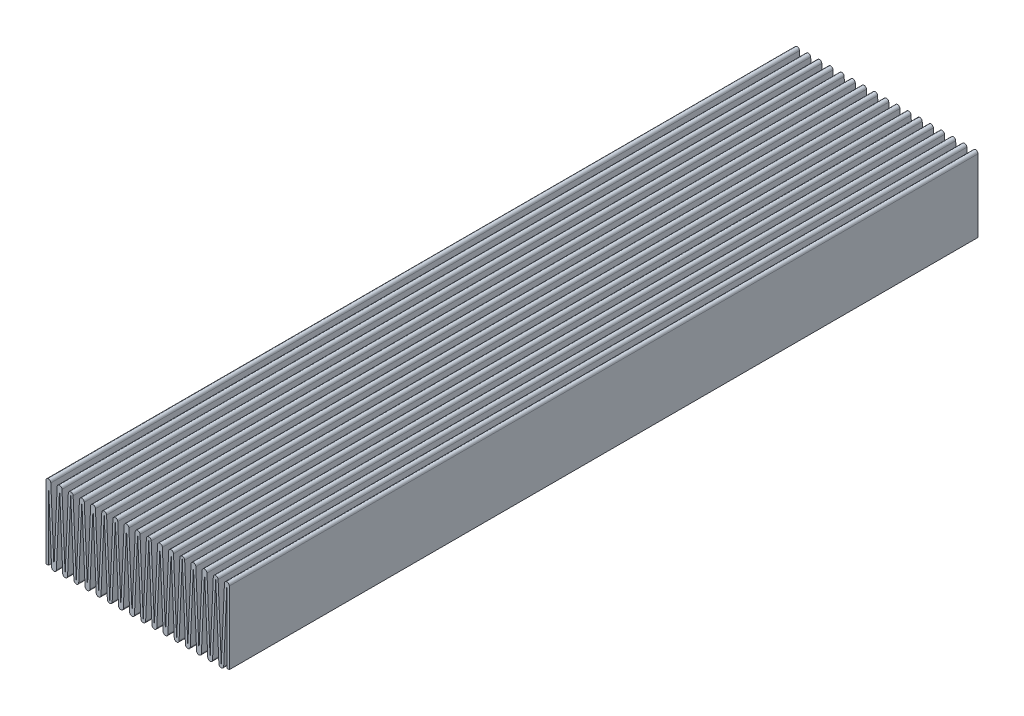
SolidWorks part; units mm, degrees
ref_plane "前视基准面" through (0, 0, 0) normal (0, 0, 1) x (1, 0, 0)
ref_plane "上视基准面" through (0, 0, 0) normal (0, 1, 0) x (1, 0, 0)
ref_plane "右视基准面" through (0, 0, 0) normal (1, 0, 0) x (0, 0, -1)
sketch "草图1" plane through (0, 0, 0) normal (0, 0, 1) x (1, 0, 0)
  line L0 (0.5, 15) -> (1.1549, 0)
  line L1 (0, 0) -> (0.5, 0)
  line L2 (0, 0) -> (0, 15)
  line L3 (0, 15) -> (0.5, 15)
  line L4 (0.5, 0) -> (0.5, 15)
  line L5 (0, 0) -> (0.5, 15) construction
  line L6 (0, 15) -> (0.5, 0) construction
  line L7 (0.5, 15) -> (0.9995, 15.0218)
  line L8 (1.1549, 0) -> (1.6544, 0.0218)
  line L9 (0.9995, 15.0218) -> (1.6544, 0.0218)
  line L10 (1.6544, 0.0218) -> (1.6544, -1.5324)
  line L11 (2.3094, 15.0218) -> (1.6544, 0.0218)
  line L12 (2.8089, 15) -> (2.154, 0)
  line L13 (2.8089, 15) -> (2.8089, 16.4409)
  line L14 (3.3084, 15.0218) -> (3.9633, 0.0218)
  line L15 (2.8089, 15) -> (3.4638, 0)
  line L16 (5.1178, 15) -> (4.4628, 0)
  line L17 (4.6182, 15.0218) -> (3.9633, 0.0218)
  line L18 (5.1178, 15) -> (5.1178, 16.4409)
  line L19 (5.6173, 15.0218) -> (6.2722, 0.0218)
  line L20 (5.1178, 15) -> (5.7727, 0)
  line L21 (7.4266, 15) -> (6.7717, 0)
  line L22 (6.9271, 15.0218) -> (6.2722, 0.0218)
  line L23 (7.9262, 15.0218) -> (8.5811, 0.0218)
  line L24 (7.4266, 15) -> (8.0815, 0)
  line L25 (9.7355, 15) -> (9.0806, 0)
  line L26 (9.236, 15.0218) -> (8.5811, 0.0218)
  line L27 (9.7355, 15) -> (9.7355, 16.4409)
  line L28 (18.971, 15) -> (18.971, 17.0964)
  line L29 (19.4705, 15.0218) -> (20.1255, 0.0218)
  line L30 (18.971, 15) -> (19.6259, 0)
  line L31 (10.235, 15.0218) -> (10.8899, 0.0218)
  line L32 (9.7355, 15) -> (10.3904, 0)
  line L33 (12.0444, 15) -> (11.3895, 0)
  line L34 (11.5449, 15.0218) -> (10.8899, 0.0218)
  line L35 (12.5439, 15.0218) -> (13.1988, 0.0218)
  line L36 (12.0444, 15) -> (12.6993, 0)
  line L37 (14.3533, 15) -> (13.6983, 0)
  line L38 (13.8537, 15.0218) -> (13.1988, 0.0218)
  line L39 (14.8528, 15.0218) -> (15.5077, 0.0218)
  line L40 (14.3533, 15) -> (15.0082, 0)
  line L41 (16.6621, 15) -> (16.0072, 0)
  line L42 (16.1626, 15.0218) -> (15.5077, 0.0218)
  line L43 (17.1617, 15.0218) -> (17.8166, 0.0218)
  line L44 (16.6621, 15) -> (17.317, 0)
  line L45 (18.971, 15) -> (18.3161, 0)
  line L46 (18.4715, 15.0218) -> (17.8166, 0.0218)
  line L47 (21.2799, 15) -> (20.625, 0)
  line L48 (20.7804, 15.0218) -> (20.1255, 0.0218)
  line L49 (21.7794, 15.0218) -> (22.4343, 0.0218)
  line L50 (21.2799, 15) -> (21.9348, 0)
  line L51 (23.5888, 15) -> (22.9339, 0)
  line L52 (23.0892, 15.0218) -> (22.4343, 0.0218)
  line L53 (24.0883, 15.0218) -> (24.7432, 0.0218)
  line L54 (23.5888, 15) -> (24.2437, 0)
  line L55 (25.3981, 15.0218) -> (24.7432, 0.0218)
  line L56 (25.8976, 15) -> (25.2427, 0)
  line L57 (26.3972, 15.0218) -> (27.0521, 0.0218)
  line L58 (25.8976, 15) -> (26.5526, 0)
  line L59 (27.707, 15.0218) -> (27.0521, 0.0218)
  line L60 (28.2065, 15) -> (27.5516, 0)
  line L61 (28.706, 15.0218) -> (29.361, 0.0218)
  line L62 (28.2065, 15) -> (28.8614, 0)
  line L63 (30.5154, 15) -> (29.8605, 0)
  line L64 (30.0159, 15.0218) -> (29.361, 0.0218)
  line L65 (31.0149, 15.0218) -> (31.6698, 0.0218)
  line L66 (30.5154, 15) -> (31.1703, 0)
  line L67 (32.8243, 15) -> (32.1694, 0)
  line L68 (32.3247, 15.0218) -> (31.6698, 0.0218)
  line L69 (33.3238, 15.0218) -> (33.9787, 0.0218)
  line L70 (32.8243, 15) -> (33.4792, 0)
  line L71 (35.1331, 15) -> (34.4782, 0)
  line L72 (34.6336, 15.0218) -> (33.9787, 0.0218)
  line L73 (35.1331, 15) -> (35.7881, 0)
  line L74 (35.6327, 15.0218) -> (36.2876, 0.0218)
  line L75 (37.442, 15) -> (36.7871, 0)
  line L76 (36.9425, 15.0218) -> (36.2876, 0.0218)
  line L77 (37.442, 0) -> (37.442, 15)
  line L78 (37.942, 0) -> (37.442, 0)
  line L79 (37.942, 0) -> (37.942, 15)
  arc A0 (0, 15) -> (0.9995, 15.0218) centre (0.5, 15) cw
  arc A1 (1.1549, 0) -> (2.154, 0) centre (1.6544, 0.0218) ccw
  arc A2 (3.3089, 15) -> (2.3094, 15.0218) centre (2.8089, 15) ccw
  arc A3 (2.3089, 15) -> (3.3084, 15.0218) centre (2.8089, 15) cw
  arc A4 (4.4628, 0) -> (3.4638, 0) centre (3.9633, 0.0218) cw
  arc A5 (5.6178, 15) -> (4.6182, 15.0218) centre (5.1178, 15) ccw
  arc A6 (4.6178, 15) -> (5.6173, 15.0218) centre (5.1178, 15) cw
  arc A7 (5.7727, 0) -> (6.7717, 0) centre (6.2722, 0.0218) ccw
  arc A8 (6.9266, 15) -> (7.9262, 15.0218) centre (7.4266, 15) cw
  arc A9 (9.0806, 0) -> (8.0815, 0) centre (8.5811, 0.0218) cw
  arc A10 (10.2355, 15) -> (9.236, 15.0218) centre (9.7355, 15) ccw
  arc A11 (9.2355, 15) -> (10.235, 15.0218) centre (9.7355, 15) cw
  arc A12 (10.3904, 0) -> (11.3895, 0) centre (10.8899, 0.0218) ccw
  arc A13 (12.5444, 15) -> (11.5449, 15.0218) centre (12.0444, 15) ccw
  arc A14 (13.6983, 0) -> (12.6993, 0) centre (13.1988, 0.0218) cw
  arc A15 (13.8533, 15) -> (14.8528, 15.0218) centre (14.3533, 15) cw
  arc A16 (15.0082, 0) -> (16.0072, 0) centre (15.5077, 0.0218) ccw
  arc A17 (16.1621, 15) -> (17.1617, 15.0218) centre (16.6621, 15) cw
  arc A18 (18.3161, 0) -> (17.317, 0) centre (17.8166, 0.0218) cw
  arc A19 (19.471, 15) -> (18.4715, 15.0218) centre (18.971, 15) ccw
  arc A20 (18.471, 15) -> (19.4705, 15.0218) centre (18.971, 15) cw
  arc A21 (19.6259, 0) -> (20.625, 0) centre (20.1255, 0.0218) ccw
  arc A22 (21.7799, 15) -> (20.7804, 15.0218) centre (21.2799, 15) ccw
  arc A23 (22.9339, 0) -> (21.9348, 0) centre (22.4343, 0.0218) cw
  arc A24 (24.0888, 15) -> (23.0892, 15.0218) centre (23.5888, 15) ccw
  arc A25 (24.2437, 0) -> (25.2427, 0) centre (24.7432, 0.0218) ccw
  arc A26 (25.3976, 15) -> (26.3972, 15.0218) centre (25.8976, 15) cw
  arc A27 (27.5516, 0) -> (26.5526, 0) centre (27.0521, 0.0218) cw
  arc A28 (27.7065, 15) -> (28.706, 15.0218) centre (28.2065, 15) cw
  arc A29 (28.8614, 0) -> (29.8605, 0) centre (29.361, 0.0218) ccw
  arc A30 (31.0154, 15) -> (30.0159, 15.0218) centre (30.5154, 15) ccw
  arc A31 (32.1694, 0) -> (31.1703, 0) centre (31.6698, 0.0218) cw
  arc A32 (32.3243, 15) -> (33.3238, 15.0218) centre (32.8243, 15) cw
  arc A33 (33.4792, 0) -> (34.4782, 0) centre (33.9787, 0.0218) ccw
  arc A34 (34.6331, 15) -> (35.6327, 15.0218) centre (35.1331, 15) cw
  arc A35 (36.7871, 0) -> (35.7881, 0) centre (36.2876, 0.0218) cw
  arc A36 (37.942, 15) -> (36.9425, 15.0218) centre (37.442, 15) ccw
  point P4 (0.25, 7.5)
  dimension "D5" = 15.0143
  dimension "D1" = 0.5
  dimension "D2" = 2.5
  dimension "D3" = 15
  dimension "D4" = 1.5542
extrude "凸台-拉伸4" add sketch "草图1" along normal blind 155
